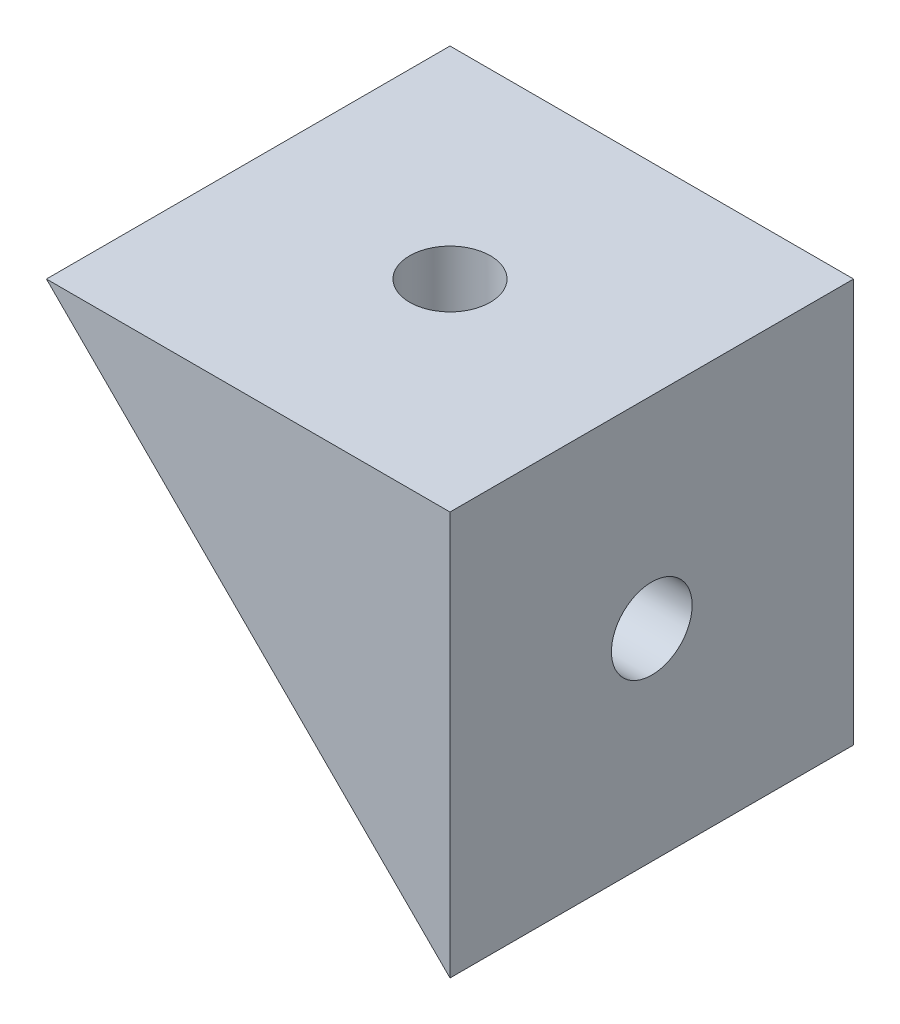
SolidWorks part; units mm, degrees
ref_plane "Front Plane" through (0, 0, 0) normal (0, 0, 1) x (1, 0, 0)
ref_plane "Top Plane" through (0, 0, 0) normal (0, 1, 0) x (1, 0, 0)
ref_plane "Right Plane" through (0, 0, 0) normal (1, 0, 0) x (0, 0, -1)
sketch "Esquisse1" plane through (0, 0, 0) normal (0, 0, 1) x (1, 0, 0)
  line L0 (0, 0) -> (-20, 0)
  line L1 (-20, 0) -> (0, -20)
  line L2 (0, -20) -> (0, 0)
  dimension "D1" = 20
  dimension "D2" = 20
extrude "Boss.-Extru.1" add sketch "Esquisse1" along normal blind 20
sketch "Esquisse2" plane through (0, 0, 0) normal (0, 1, 0) x (1, 0, 0)
  line L0 (-10, 0) -> (-10, -20) construction
  line L1 (0, 0) -> (-20, 0) construction
  line L2 (0, -20) -> (-20, -20) construction
  circle A0 centre (-10, -10) radius 2
extrude "Enlèv. mat.-Extru.1" cut sketch "Esquisse2" against normal through all
sketch "Esquisse3" plane through (0, 0, 0) normal (1, 0, 0) x (0, 0, -1)
  line L0 (-20, -10) -> (0, -10) construction
  line L1 (-20, -20) -> (-20, 0) construction
  line L2 (0, -20) -> (0, 0) construction
  circle A0 centre (-10, -10) radius 2
extrude "Enlèv. mat.-Extru.2" cut sketch "Esquisse3" against normal through all
ref_plane "Plan1" through (0, -10, 0) normal (0, 1, 0) x (1, 0, 0)
sketch "Esquisse6" plane through (0, -10, 0) normal (0, 1, 0) x (1, 0, 0)
  line L0 (-10.004, 0) -> (-10.004, -19.9894) construction
  circle A0 centre (-10.004, -9.9947) radius 5
extrude "Enlèv. mat.-Extru.3" cut sketch "Esquisse6" against normal blind 5 and the other way blind 5
ref_plane "Plan2" through (-10, 0, 0) normal (1, 0, 0) x (0, 0, -1)
sketch "Esquisse9" plane through (-10, 0, 0) normal (1, 0, 0) x (0, 0, -1)
  line L0 (0, -10.0419) -> (-19.939, -10.0419) construction
  circle A0 centre (-9.9695, -10.0419) radius 5
extrude "Enlèv. mat.-Extru.4" cut sketch "Esquisse9" against normal blind 5 and the other way blind 6
